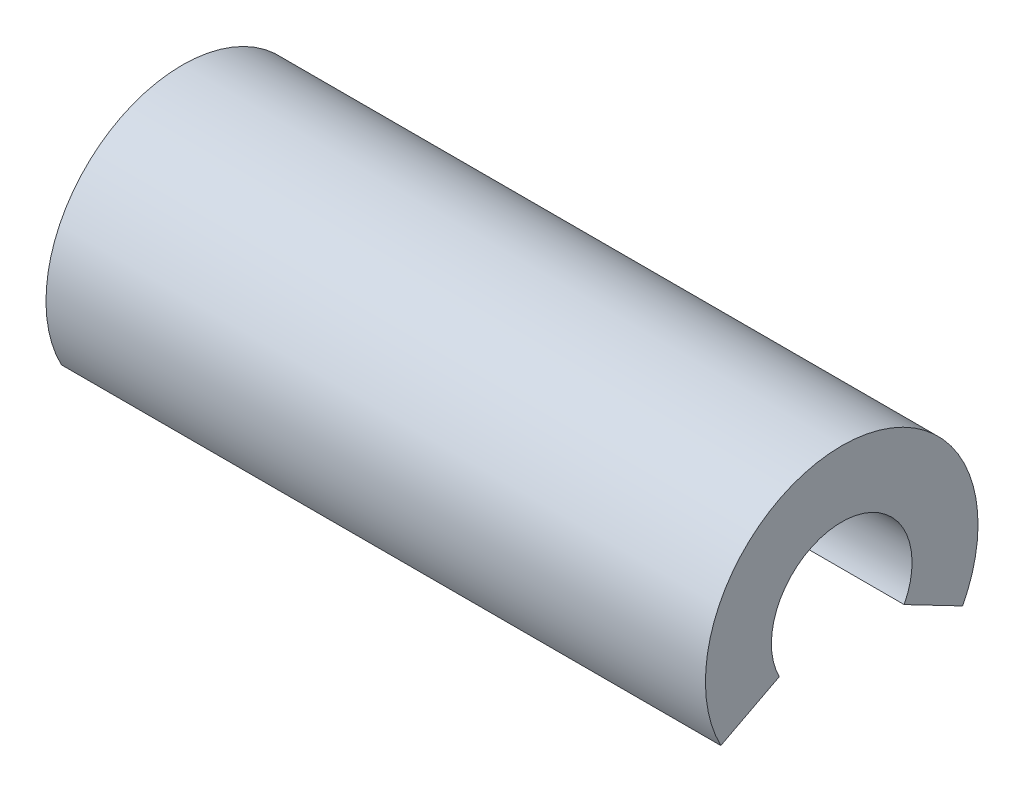
SolidWorks part; units mm, degrees
ref_plane "Front Plane" through (0, 0, 0) normal (0, 0, 1) x (1, 0, 0)
ref_plane "Top Plane" through (0, 0, 0) normal (0, 1, 0) x (1, 0, 0)
ref_plane "Right Plane" through (0, 0, 0) normal (1, 0, 0) x (0, 0, -1)
sketch "Sketch1" plane through (0, 0, 0) normal (1, 0, 0) x (0, 0, -1)
  line L0 (-5.5, -2.8618) -> (-2.8387, -1.4771)
  line L1 (2.8387, -1.4771) -> (5.5, -2.8618)
  line L2 (-5.2298, -3.3811) -> (-22690.299, 43594.0447) construction
  line L3 (5.1194, -3.5933) -> (22981.4626, 44153.619) construction
  arc A0 (-2.8387, -1.4771) -> (2.8387, -1.4771) centre (0, 0) cw
  arc A1 (5.5, -2.8618) -> (-5.5, -2.8618) centre (0, 0) ccw
  point P6 (-5.1504, -3.4057)
  point P9 (0, 0)
  point P12 (-5.4529, -2.9505)
  dimension "D1" = 3.2
  dimension "D2" = 3
  dimension "D3" = 11
extrude "Boss-Extrude1" add sketch "Sketch1" along normal blind 30
